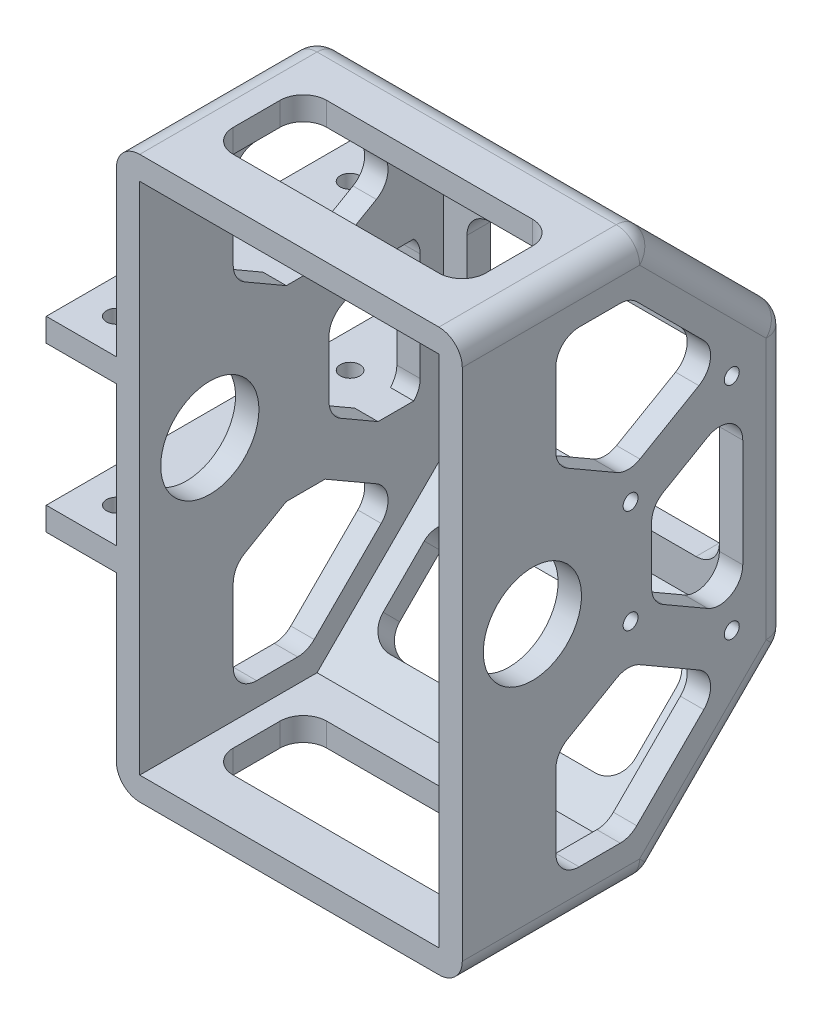
SolidWorks part; units mm, degrees
ref_plane "正面" through (0, 0, 0) normal (0, 0, 1) x (1, 0, 0)
ref_plane "平面" through (0, 0, 0) normal (0, 1, 0) x (1, 0, 0)
ref_plane "右側面" through (0, 0, 0) normal (1, 0, 0) x (0, 0, -1)
sketch "ｽｹｯﾁ1" plane through (0, 0, 0) normal (0, 0, 1) x (1, 0, 0)
  line L1 (-37, 60) -> (37, 60)
  line L2 (-37, 60) -> (-37, -60)
  line L3 (-37, -60) -> (37, -60)
  line L4 (37, 60) -> (37, -60)
  line L5 (-37, 60) -> (37, -60) construction
  line L6 (-37, -60) -> (37, 60) construction
  point P0 (0, 0)
  dimension "D1" = 120
  dimension "D2" = 74
extrude "ﾎﾞｽ - 押し出し1" add sketch "ｽｹｯﾁ1" along normal blind 70
chamfer "面取り2" distance 30 angle 45 2 edges at (0, 60, 0) (0, -60, 0)
sketch "ｽｹｯﾁ2" plane through (-37, 0, 0) normal (-1, 0, 0) x (0, 0, 1)
  line L0 (70, 60) -> (70, -60) construction
  line L1 (55, -23.6714) -> (55, -60)
  line L2 (55, 23.6714) -> (34.5, 11.8357)
  line L3 (34.5, 11.8357) -> (34.5, -11.8357)
  line L4 (34.5, -11.8357) -> (55, -23.6714)
  line L5 (55, -23.6714) -> (75.5, -11.8357)
  line L6 (75.5, -11.8357) -> (75.5, 11.8357)
  line L7 (75.5, 11.8357) -> (55, 23.6714)
  line L8 (70, -60) -> (30, -60) construction
  line L9 (34.5, -11.8357) -> (1.1122, -31.1122)
  line L10 (50, -23.6714) -> (50, -60)
  line L11 (0, -30) -> (30, -60) construction
  line L12 (55, 23.6714) -> (55, 60)
  line L13 (70, 60) -> (30, 60) construction
  line L14 (34.5, 11.8357) -> (1.1122, 31.1122)
  line L15 (30, 60) -> (0, 30) construction
  line L16 (32, -16.1658) -> (52.5, -28.0015)
  line L17 (32, -7.5056) -> (-1.3878, -26.782)
  line L18 (57.5, -28.0015) -> (80.5, -14.7224)
  line L19 (80.5, -14.7224) -> (80.5, 14.7224)
  line L20 (80.5, 14.7224) -> (57.5, 28.0015)
  line L21 (29.5, 11.8357) -> (29.5, -11.8357)
  line L22 (37, 16.1658) -> (3.6122, 35.4423)
  line L23 (52.5, 28.0015) -> (32, 16.1658)
  line L24 (60, 23.6714) -> (60, 60)
  line L25 (60, -23.6714) -> (60, -60)
  line L26 (37, -7.5056) -> (57.5, -19.3412)
  line L27 (37, -16.1658) -> (3.6122, -35.4423)
  line L28 (52.5, -19.3412) -> (70.5, -8.9489)
  line L29 (70.5, -8.9489) -> (70.5, 8.9489)
  line L30 (70.5, 8.9489) -> (52.5, 19.3412)
  line L31 (39.5, 11.8357) -> (39.5, -11.8357)
  line L32 (32, 7.5056) -> (-1.3878, 26.782)
  line L33 (57.5, 19.3412) -> (37, 7.5056)
  line L34 (50, 23.6714) -> (50, 60)
  line L47 (60, 50) -> (34.1421, 50)
  line L48 (34.1421, 50) -> (10, 25.8579)
  line L49 (10, 25.8579) -> (10, -25.8579)
  line L50 (10, -25.8579) -> (34.1421, -50)
  line L51 (34.1421, -50) -> (60, -50)
  line L52 (60, -50) -> (60, 50)
  line L53 (60, 50) -> (34.1421, 50)
  line L54 (34.1421, 50) -> (10, 25.8579)
  line L55 (10, 25.8579) -> (10, -25.8579)
  line L56 (10, -25.8579) -> (34.1421, -50)
  line L57 (34.1421, -50) -> (60, -50)
  line L58 (60, -50) -> (60, 50)
  circle A0 centre (55, 0) radius 10.5
  circle A1 centre (55, 0) radius 20.5 construction
  dimension "D1" = 21
  dimension "D2" = 15
  dimension "D3" = 41
  dimension "D4" = 5
  dimension "D5" = 5
  dimension "D6" = 10
shell "ｼｪﾙ1" thickness 5
extrude "ｶｯﾄ - 押し出し1" cut sketch "ｽｹｯﾁ2" against normal through all contours L56 L57 L10 L16 L27 | L32 L55 L17 L21 | L53 L54 L22 L23 L34 | L58 A0 | L58 A0
sketch "ｽｹｯﾁ3" plane through (0, -15, -15) normal (0, -0.7071, -0.7071) x (1, 0, 0)
  line L8 (-27, 53.6396) -> (-27, 31.2132)
  line L9 (-27, 31.2132) -> (27, 31.2132)
  line L10 (27, 31.2132) -> (27, 53.6396)
  line L11 (27, 53.6396) -> (-27, 53.6396)
  line L12 (-27, 53.6396) -> (-27, 31.2132)
  line L13 (-27, 31.2132) -> (27, 31.2132)
  line L14 (27, 31.2132) -> (27, 53.6396)
  line L15 (27, 53.6396) -> (-27, 53.6396)
  dimension "D1" = 10
extrude "ｶｯﾄ - 押し出し2" cut sketch "ｽｹｯﾁ3" against normal blind 70
sketch "ｽｹｯﾁ4" plane through (0, 15, -15) normal (0, 0.7071, -0.7071) x (1, 0, 0)
  line L8 (27, -53.6396) -> (27, -31.2132)
  line L9 (27, -31.2132) -> (-27, -31.2132)
  line L10 (-27, -31.2132) -> (-27, -53.6396)
  line L11 (-27, -53.6396) -> (27, -53.6396)
  line L12 (27, -53.6396) -> (27, -31.2132)
  line L13 (27, -31.2132) -> (-27, -31.2132)
  line L14 (-27, -31.2132) -> (-27, -53.6396)
  line L15 (-27, -53.6396) -> (27, -53.6396)
  dimension "D1" = 10
extrude "ｶｯﾄ - 押し出し3" cut sketch "ｽｹｯﾁ4" against normal blind 70
sketch "ｽｹｯﾁ5" plane through (0, 0, 0) normal (0, 0, -1) x (-1, 0, 0)
  line L8 (27, -20) -> (27, 20)
  line L9 (27, 20) -> (-27, 20)
  line L10 (-27, 20) -> (-27, -20)
  line L11 (-27, -20) -> (27, -20)
  line L12 (27, -20) -> (27, 20)
  line L13 (27, 20) -> (-27, 20)
  line L14 (-27, 20) -> (-27, -20)
  line L15 (-27, -20) -> (27, -20)
  dimension "D1" = 10
extrude "ｶｯﾄ - 押し出し4" cut sketch "ｽｹｯﾁ5" against normal blind 70
sketch "ｽｹｯﾁ7" plane through (0, 60, 0) normal (0, 1, 0) x (1, 0, 0)
  line L8 (27, -60) -> (27, -40)
  line L9 (27, -40) -> (-27, -40)
  line L10 (-27, -40) -> (-27, -60)
  line L11 (-27, -60) -> (27, -60)
  line L12 (27, -60) -> (27, -40)
  line L13 (27, -40) -> (-27, -40)
  line L14 (-27, -40) -> (-27, -60)
  line L15 (-27, -60) -> (27, -60)
  dimension "D1" = 10
extrude "ｶｯﾄ - 押し出し5" cut sketch "ｽｹｯﾁ7" against normal through all
fillet "ﾌｨﾚｯﾄ1" radius 5 62 edges at (27, 51.1612, 24.6967) (-27, 51.1612, 24.6967) (-27, 35.3033, 8.8388) (27, 35.3033, 8.8388) (-27, 20, 2.5) (-27, -20, 2.5) (27, 20, 2.5) (27, -20, 2.5) (-27, -35.3033, 8.8388) (-27, -51.1612, 24.6967) (27, -51.1612, 24.6967) (27, -35.3033, 8.8388) (34.5, -50, 34.1421) (34.5, -29.596, 13.7382) (34.5, -17.6092, 34.5) (34.5, -26.5581, 50) (34.5, -50, 50) (34.5, 26.5581, 50) (34.5, 17.6092, 34.5) (34.5, 29.596, 13.7382) (34.5, 50, 34.1421) (34.5, 50, 50) (34.5, -20.2073, 10) (34.5, -8.9489, 29.5) (34.5, 8.9489, 29.5) (34.5, 20.2073, 10) (-34.5, 29.596, 13.7382) (-34.5, 50, 34.1421) (-34.5, 50, 50) (-34.5, 26.5581, 50) (-34.5, 17.6092, 34.5) (-34.5, 20.2073, 10) (-34.5, 8.9489, 29.5) (-34.5, -20.2073, 10) (-34.5, -8.9489, 29.5) (-34.5, -29.596, 13.7382) (-34.5, -17.6092, 34.5) (-34.5, -26.5581, 50) (-34.5, -50, 50) (-34.5, -50, 34.1421) (-27, -57.5, 60) (-27, -57.5, 40) (27, -57.5, 40) (27, -57.5, 60) (27, 57.5, 60) (27, 57.5, 40) (-27, 57.5, 40) (-27, 57.5, 60) (37, -45, 15) (37, -60, 50) (-37, -60, 50) (-37, -45, 15) (0, -30, 0) (-37, 0, 0) (-37, 45, 15) (0, 60, 30) (-37, 60, 50) (37, 60, 50) (0, 30, 0) (37, 45, 15) (37, 0, 0) (0, -60, 30)
sketch "ｽｹｯﾁ10" plane through (-37, 0, 0) normal (-1, 0, 0) x (0, 0, 1)
  line L0 (5, 27.9289) -> (5, -27.9289) construction
  line L1 (70, 17.5) -> (5, 17.5)
  line L2 (70, 17.5) -> (70, -17.5)
  line L3 (70, -17.5) -> (5, -17.5)
  line L4 (5, 17.5) -> (5, -17.5)
  line L5 (70, 17.5) -> (5, -17.5) construction
  line L6 (70, -17.5) -> (5, 17.5) construction
  line L7 (70, 55) -> (70, -55) construction
  line L8 (70, -15) -> (5, -15)
  line L9 (70, 20) -> (5, 20)
  line L10 (70, -20) -> (5, -20)
  line L11 (70, 15) -> (5, 15)
  line L13 (5, -15) -> (0, -15)
  line L14 (5, -15) -> (5, -20)
  line L15 (5, -20) -> (0, -20)
  line L16 (0, -15) -> (0, -20)
  line L17 (2.5, -20) -> (2.5, -15) construction
  line L18 (5, -17.5) -> (0, -17.5) construction
  line L19 (5, 20) -> (0, 20)
  line L20 (5, 20) -> (5, 15)
  line L21 (5, 15) -> (0, 15)
  line L22 (0, 20) -> (0, 15)
  line L23 (2.5, 15) -> (2.5, 20) construction
  line L24 (5, 17.5) -> (0, 17.5) construction
  circle A0 centre (55, 0) radius 10.5 construction
  point P0 (37.5, 0)
  point P110 (2.5, -17.5)
  point P114 (2.5, 17.5)
  line M12 (47.5, 25.1147) -> (37, 19.0526)
  arc M13 (37, 19.0526) -> (32, 19.0526) centre (34.5, 23.3827) cw
  line M14 (32, 19.0526) -> (19.3813, 26.338)
  arc M17 (10, 11.547) -> (17.5, 15.8771) centre (15, 11.547) cw
  line M18 (17.5, 15.8771) -> (27, 10.3923)
  line M22 (27, -10.3923) -> (17.5, -15.8771)
  arc M23 (17.5, -15.8771) -> (10, -11.547) centre (15, -11.547) cw
  line M28 (19.3813, -26.338) -> (32, -19.0526)
  arc M29 (32, -19.0526) -> (37, -19.0526) centre (34.5, -23.3827) cw
  line M30 (37, -19.0526) -> (47.5, -25.1147)
  line M36 (70, -55) -> (70, 55)
  line M39 (5, 27.9289) -> (5, -27.9289)
  dimension "D1" = 0
  dimension "D2" = 35
  dimension "D3" = 0
  dimension "D4" = 2.5
  dimension "D5" = 2.5
extrude "ﾎﾞｽ - 押し出し3" add sketch "ｽｹｯﾁ10" along normal blind 15 and the other way blind 5 contours L8 L4 L3 M36 M22 M23 | L10 L3 M36 M39 M28 M29 M30 | L11 L1 M36 M39 M17 M18 | L9 L1 M36 M12 M13 M14 M39 | L10 M30 M29 M28 | L9 M12 M14 M13 | L8 M22 M23 | L11 M18 M17 | L19 L22 L21 M39 | L13 L16 L15 L4 M39
sketch "ｽｹｯﾁ12" plane through (0, -20, 0) normal (0, -1, 0) x (1, 0, 0)
  line L1 (-37, 70) -> (-52, 70) construction
  line L2 (-52, 70) -> (-52, 0) construction
  circle A0 centre (-44.5, 62.5) radius 2.1
  circle A1 centre (-44.5, 12.5) radius 2.1
  dimension "D1" = 7.5
  dimension "D2" = 7.5
  dimension "D3" = 4.2
  dimension "D4" = 50
  dimension "D5" = 4.2
extrude "ｶｯﾄ - 押し出し7" cut sketch "ｽｹｯﾁ12" against normal through all
sketch "ｽｹｯﾁ13" plane through (37, 0, 0) normal (1, 0, 0) x (0, 0, -1)
  circle A0 centre (-12.3494, 24.6244) radius 1.6
  circle A1 centre (-34, 12.1244) radius 1.6
  circle A2 centre (-34, -10.0111) radius 1.6
  circle A3 centre (-12.3494, -22.5111) radius 1.6
extrude "ｶｯﾄ - 押し出し8" cut sketch "ｽｹｯﾁ13" against normal blind 10
